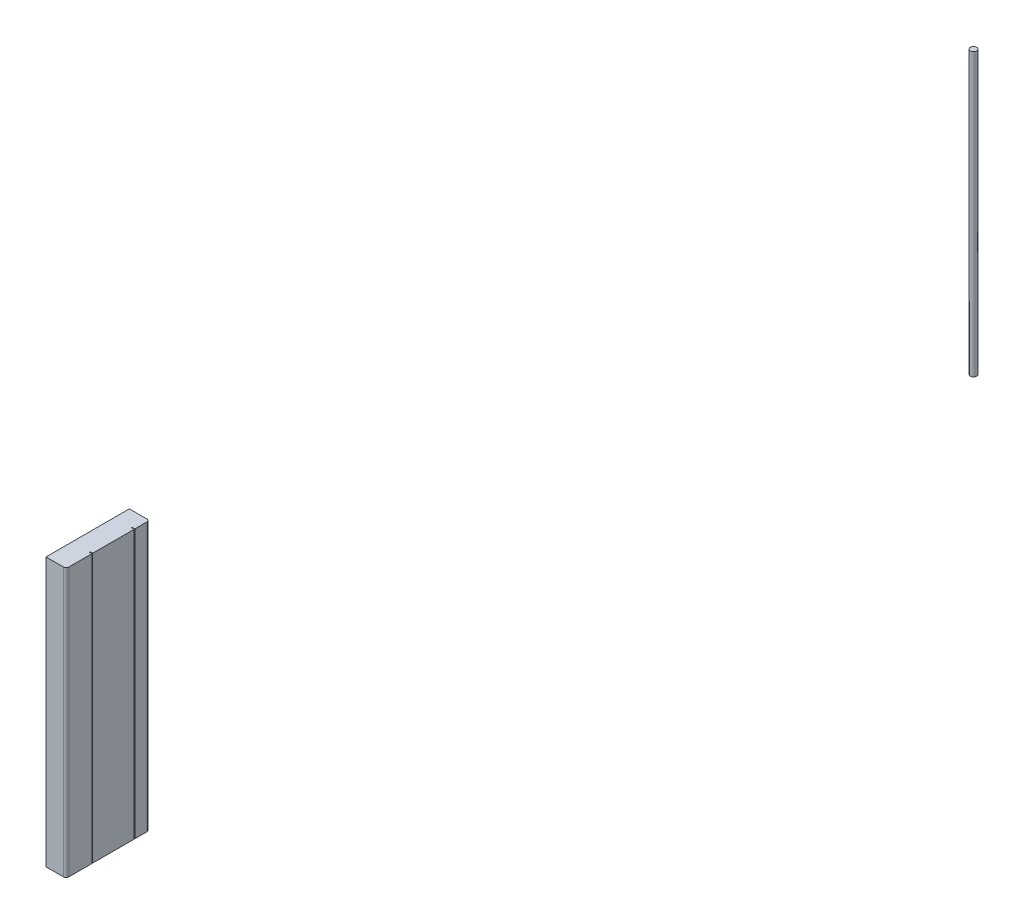
SolidWorks part; units mm, degrees
material "EPDM"
ref_plane "Спереди" through (0, 0, 0) normal (0, 0, 1) x (1, 0, 0)
ref_plane "Сверху" through (0, 0, 0) normal (0, 1, 0) x (1, 0, 0)
ref_plane "Справа" through (0, 0, 0) normal (1, 0, 0) x (0, 0, -1)
sketch "Эскиз1" plane through (0, 0, 0) normal (1, 0, 0) x (0, 0, -1)
  line L1 (-58.8018, 192.3212) -> (3.2982, 192.3212)
  line L2 (-58.8018, 192.3212) -> (-58.8018, -7.6788)
  line L3 (-58.8018, -7.6788) -> (3.2982, -7.6788)
  line L4 (3.2982, 192.3212) -> (3.2982, -7.6788)
  dimension "D1" = 200
  dimension "D2" = 62.1
extrude "Бобышка-Вытянуть1" add sketch "Эскиз1" along normal blind 15
sketch "Эскиз2" plane through (0, 192.3212, 0) normal (0, 1, 0) x (1, 0, 0)
  line L0 (15, 3.2982) -> (15, -58.8018) construction
  line L1 (13, -39.0018) -> (15, -39.0018)
  line L2 (13, -39.0018) -> (13, -39.5018)
  line L3 (13, -39.5018) -> (15, -39.5018)
  line L4 (15, -39.0018) -> (15, -39.5018)
  line L5 (13, -7.6018) -> (15, -7.6018)
  line L6 (13, -7.6018) -> (13, -8.1018)
  line L7 (13, -8.1018) -> (15, -8.1018)
  line L8 (15, -7.6018) -> (15, -8.1018)
  dimension "D1" = 0.5
  dimension "D2" = 2
  dimension "D3" = 19.3
  dimension "D4" = 50.7
extrude "Вырез-Вытянуть1" cut sketch "Эскиз2" against normal through all
fillet "Скругление1" radius 2 2 edges at (15, 92.3212, -3.2982) (15, 92.3212, 58.8018)
sketch "Эскиз3" plane through (0, 0, 0) normal (0, 1, 0) x (1, 0, 0)
  circle A0 centre (25.5, 606.8982) radius 2.36
extrude "Бобышка-Вытянуть2" add sketch "Эскиз3" along normal blind 210 from offset 10 separate body
